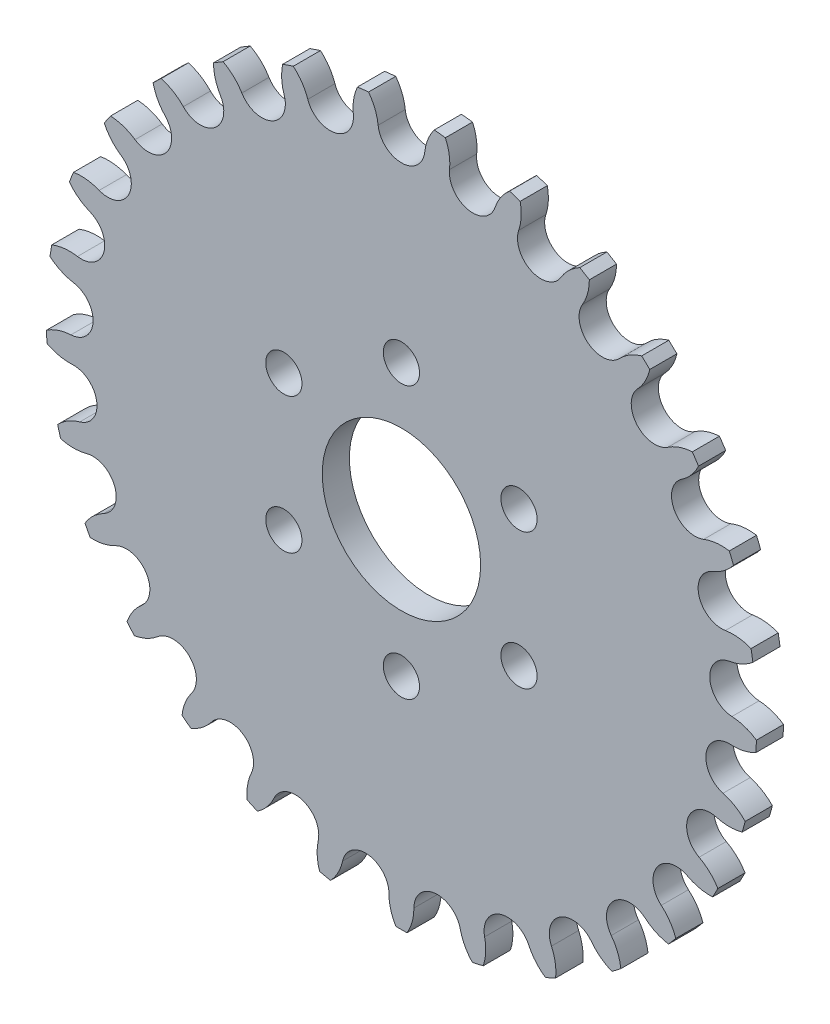
SolidWorks part; units mm, degrees
material "AISI 1020"
ref_plane "Спереди" through (0, 0, 0) normal (0, 0, 1) x (1, 0, 0)
ref_plane "Сверху" through (0, 0, 0) normal (0, 1, 0) x (1, 0, 0)
ref_plane "Справа" through (0, 0, 0) normal (1, 0, 0) x (0, 0, -1)
sketch "Эскиз1" plane through (0, 0, 0) normal (0, 0, 1) x (1, 0, 0)
  line L0 (0, 0) -> (0, 85) construction
  line L1 (0, 85) -> (15.8056, 83.5176) construction
  line L2 (15.8056, 83.5176) -> (0, 0) construction
  line L3 (15.8056, 83.5176) -> (49.3989, 83.5176)
  line L4 (0, 0) -> (0, 73.4145)
  line L5 (0, 73.4145) -> (15.7819, 71.6981)
  line L6 (15.7819, 71.6981) -> (0, 0)
  circle A0 centre (0, 0) radius 85 construction
  circle A1 centre (0, 73.4145) radius 5.08
  circle A2 centre (15.7819, 71.6981) radius 5.08
  dimension "D1" = 170
  dimension "D6" = 10.16
  dimension "D2" = 15.875
  dimension "D3" = 10.716
  dimension "D4" = 33.5932
  dimension "D5" = 12.414
sketch "Эскиз2" plane through (0, 0, 0) normal (0, 0, 1) x (1, 0, 0)
  line L0 (0, 0) -> (0, 68.2345)
  line L1 (0, 0) -> (14.6684, 66.6392)
  line L4 (15.7819, 71.6981) -> (0, 0) construction
  arc A0 (10.6323, 72.2581) -> (9.713, 77.8912) centre (0, 73.4145) ccw
  arc A1 (0, 78.4945) -> (16.874, 76.6593) centre (0, 0) cw construction
  circle A2 centre (0, 73.4145) radius 5.08 construction
  circle A3 centre (15.7819, 71.6981) radius 5.08 construction
  circle A4 centre (0, 0) radius 85 construction
  circle A5 centre (0, 73.4145) radius 5.18
  arc A6 (0, 68.2345) -> (5.1496, 72.8544) centre (0, 73.4145) ccw
  arc A7 (7.2584, 78.1582) -> (5.1496, 72.8544) centre (15.7819, 71.6981) ccw
  circle A8 centre (15.7819, 71.6981) radius 5.18
  arc A9 (10.6323, 72.2581) -> (14.6684, 66.6392) centre (15.7819, 71.6981) ccw
  arc A10 (7.2584, 78.1582) -> (9.713, 77.8912) centre (0, 0) cw
  dimension "D1" = 0.1
  dimension "D2" = 0.1
extrude "Бобышка-Вытянуть1" add sketch "Эскиз2" along normal blind 6
pattern_circular "Круговой массив1" count 29 over 360 about axis through (0, 0, 0) along (0, 0, 1) of "Бобышка-Вытянуть1"
sketch "Эскиз3" plane through (0, 0, 6) normal (0, 0, 1) x (1, 0, 0)
  line L0 (0, 0) -> (0, 30) construction
  line L1 (0, 0) -> (25.9808, 15) construction
  circle A0 centre (0, 0) radius 17.5
  circle A1 centre (0, 0) radius 30 construction
  circle A2 centre (0, 30) radius 4
  circle A3 centre (25.9808, 15) radius 4
  circle A4 centre (25.9808, -15) radius 4
  circle A5 centre (0, -30) radius 4
  circle A6 centre (-25.9808, -15) radius 4
  circle A7 centre (-25.9808, 15) radius 4
  dimension "D1" = 35
  dimension "D2" = 60
  dimension "D3" = 8
  dimension "D5" = 60
  dimension "D6" = 30
  dimension "D4" = 6
extrude "Вырез-Вытянуть1" cut sketch "Эскиз3" against normal through all
equation "\"D4@Эскиз1\"=360/\"D3@Эскиз1\""
equation "\"D5@Эскиз1\"=360/29"
